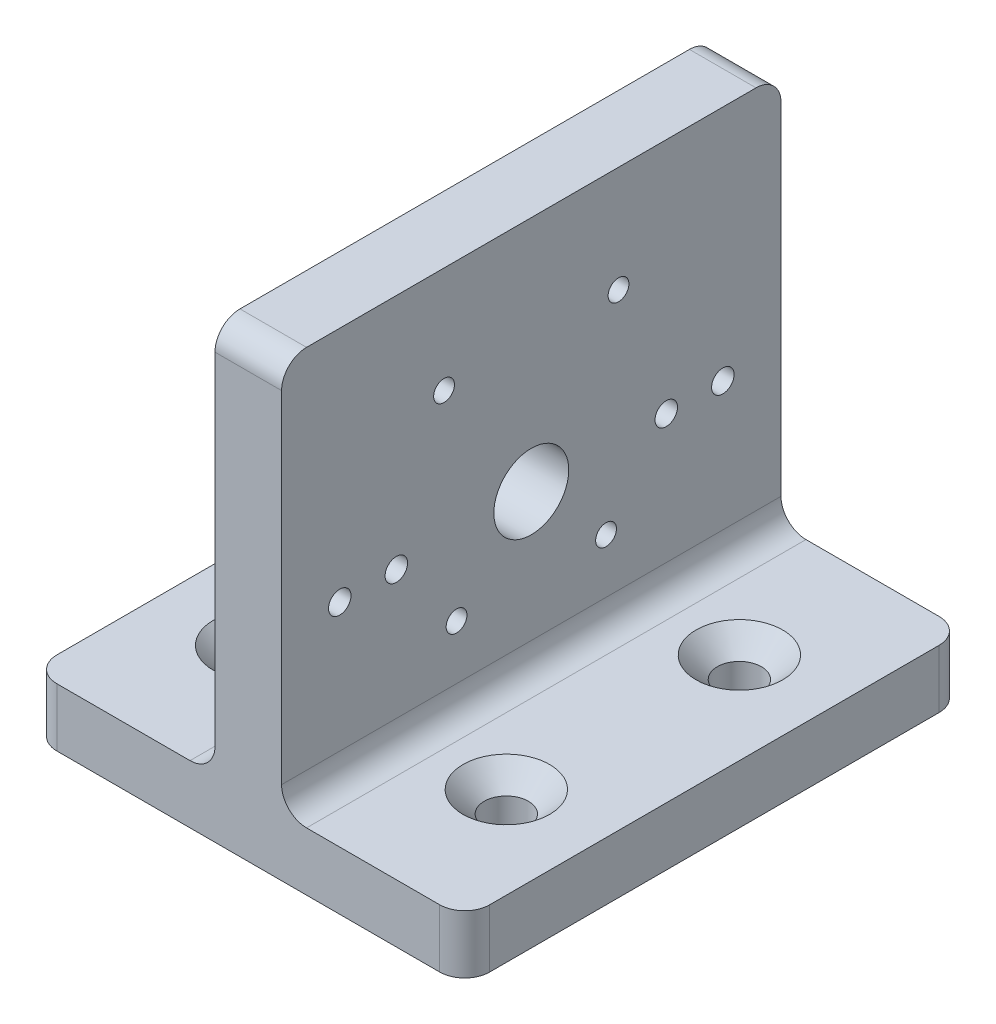
SolidWorks part; units mm, degrees
material "ABS"
ref_plane "Front Plane" through (0, 0, 0) normal (0, 0, 1) x (1, 0, 0)
ref_plane "Top Plane" through (0, 0, 0) normal (0, 1, 0) x (1, 0, 0)
ref_plane "Right Plane" through (0, 0, 0) normal (1, 0, 0) x (0, 0, -1)
sketch "Sketch1" plane through (0, 0, 0) normal (0, 0, 1) x (1, 0, 0)
  line L0 (-4, 7) -> (-26, 7)
  line L1 (-4, 54) -> (4, 54)
  line L2 (-4, 54) -> (-4, 7)
  line L4 (4, 54) -> (4, 7)
  line L14 (4, 7) -> (26, 7)
  line L16 (-26, 0) -> (-26, 7)
  line L17 (26, 0) -> (26, 7)
  line L18 (-26, 0) -> (26, 0)
  dimension "D1" = 7
  dimension "D2" = 47
  dimension "D3" = 22
  dimension "D4" = 8
extrude "Boss-Extrude1" add sketch "Sketch1" along normal blind 60
fillet "Fillet1" radius 3 8 edges at (0, 54, 0) (0, 54, 60) (26, 3.5, 0) (26, 3.5, 60) (-26, 3.5, 0) (-26, 3.5, 60) (4, 7, 30) (-4, 7, 30)
sketch "Sketch2" plane through (4, 0, 0) normal (1, 0, 0) x (0, 0, -1)
  line L1 (-30, 25.5) -> (-30, 10) construction
  line L4 (-60, 10) -> (0, 10) construction
  circle A2 centre (-30, 25.5) radius 4.5
  dimension "D1" = 9
  dimension "D2" = 15.5
extrude "Cut-Extrude1" cut sketch "Sketch2" against normal up to surface (8 mm away) up to face at (-4, 38.5404, 30)
sketch "Sketch3" plane through (4, 0, 0) normal (1, 0, 0) x (0, 0, -1)
  line L0 (-30, 25.5) -> (-53.0125, 25.5) construction
  line L1 (-30, 25.5) -> (-30, 48.5125) construction
  circle A0 centre (-30, 25.5) radius 16.215 construction
  circle A1 centre (-30, 25.5) radius 23.0125 construction
  circle A2 centre (-46.215, 25.5) radius 1.5
  circle A3 centre (-53.0125, 25.5) radius 1.435
  circle A4 centre (-6.9875, 25.5) radius 1.435
  circle A5 centre (-13.785, 25.5) radius 1.5
  dimension "D1" = 32.43
  dimension "D2" = 46.025
  dimension "D3" = 3
  dimension "D4" = 2.87
hole_wizard "Tap Drill for M3 Tap1" positions "3DSketch1" profile "Sketch4" hole size "M3" standard "ISO" end condition through all
sketch3d "3DSketch1"
  point P0 (4, 25.5, 46.215)
  point P3 (4, 25.5, 13.785)
  point P6 (4, 25.5, 53.0125)
  point P9 (4, 25.5, 6.9875)
sketch "Sketch4" plane through (4, 25.5, 46.215) normal (0, 1, 0) x (0, 0, -1)
  line L0 (0, 0) -> (0, 30)
  line L1 (0, 30) -> (1.35, 30)
  line L2 (1.35, 30) -> (1.35, 0)
  line L5 (1.35, 0) -> (0, 0)
  line L11 (0, -6.35) -> (0, 107.95) construction
  dimension "Thru Hole Dia." = 2.7
  dimension "Thru Hole Depth" = 30
sketch "Sketch5" plane through (0, 7, 0) normal (0, 1, 0) x (1, 0, 0)
  line L0 (-15, 0) -> (-15, -16) construction
  line L6 (-7, 0) -> (-23, 0) construction
  line L9 (-15, -16) -> (-15, -44) construction
  line L10 (-15, -44) -> (-15, -60) construction
  line L12 (-7, -60) -> (-23, -60) construction
  line L14 (15, 0) -> (15, -16) construction
  line L15 (7, 0) -> (23, 0) construction
  line L16 (15, -16) -> (15, -44) construction
  line L18 (15, -44) -> (15, -60) construction
  line L19 (7, -60) -> (23, -60) construction
  circle A0 centre (-15, -16) radius 2.5
  circle A1 centre (-15, -44) radius 2.5
  circle A2 centre (15, -16) radius 2.5
  circle A3 centre (15, -44) radius 2.5
  dimension "D1" = 5
  dimension "D2" = 5
  dimension "D3" = 5
  dimension "D4" = 5
  dimension "D5" = 16
sketch "Sketch11" plane through (4, 0, 0) normal (1, 0, 0) x (0, 0, -1)
  line L0 (-30, 25.5) -> (-30, 12.8) construction
  line L1 (-30, 25.5) -> (-21.0197, 16.5197) construction
  line L2 (-30, 25.5) -> (-38.9803, 16.5197) construction
  line L3 (-30, 25.5) -> (-30, 41.25) construction
  line L4 (-30, 25.5) -> (-30, 48.5125) construction
  line L5 (-40.48, 41.25) -> (-19.52, 41.25) construction
  circle A0 centre (-30, 25.5) radius 12.7 construction
  dimension "D1" = 25.4
  dimension "D2" = 45
  dimension "D3" = 45
  dimension "D4" = 15.75
  dimension "D5" = 20.96
hole_wizard "Tap Drill for M3 Tap2" positions "3DSketch2" profile "Sketch12" hole size "M3" standard "DIN" end condition through all
sketch3d "3DSketch2"
  point P0 (4, 41.25, 40.48)
  point P3 (4, 41.25, 19.52)
  point P6 (4, 16.5197, 21.0197)
  point P9 (4, 16.5197, 38.9803)
sketch "Sketch12" plane through (4, 41.25, 40.48) normal (0, 1, 0) x (0, 0, -1)
  line L0 (0, 0) -> (0, 30)
  line L1 (0, 30) -> (1.25, 30)
  line L2 (1.25, 30) -> (1.25, 0)
  line L5 (1.25, 0) -> (0, 0)
  line L11 (0, -6.35) -> (0, 107.95) construction
  dimension "Thru Hole Dia." = 2.5
  dimension "Thru Hole Depth" = 30
hole_wizard "CSK for M5 Countersunk Raised Head Screw1" positions "3DSketch3" profile "Sketch13" countersink size "M5" standard "ISO" end condition through all
sketch3d "3DSketch3"
  point P0 (-15, 7, 16)
  point P3 (-15, 7, 44)
  point P6 (15, 7, 44)
  point P9 (15, 7, 16)
sketch "Sketch13" plane through (-15, 7, 16) normal (1, 0, 0) x (0, 0, 1)
  line L0 (0, 0) -> (0, 7)
  line L1 (0, 7) -> (2.65, 7)
  line L2 (2.65, 7) -> (2.65, 2.55)
  line L3 (2.65, 2.55) -> (5.2, 0)
  line L5 (5.2, 0) -> (0, 0)
  line L6 (-2.65, 2.55) -> (-5.2, 0) construction
  line L11 (0, -6.35) -> (0, 107.95) construction
  dimension "Thru Hole Dia." = 5.3
  dimension "Thru Hole Depth" = 7
  dimension "Near C'Sink Dia." = 10.4
  dimension "Near C'Sink Angle" = 90
